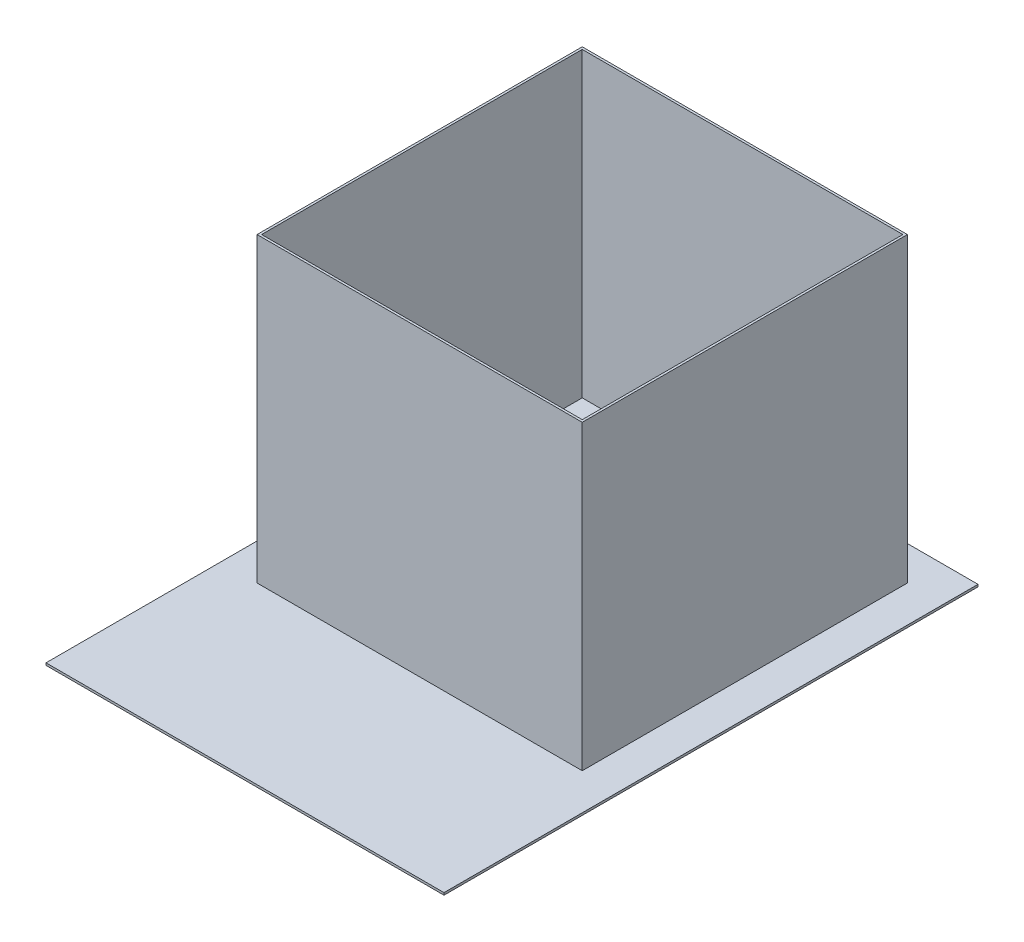
SolidWorks part; units mm, degrees
material "AISI 304"
ref_plane "Front" through (0, 0, 0) normal (0, 0, 1) x (1, 0, 0)
ref_plane "Top" through (0, 0, 0) normal (0, 1, 0) x (1, 0, 0)
ref_plane "Right" through (0, 0, 0) normal (1, 0, 0) x (0, 0, -1)
sketch "Croquis1" plane through (0, 0, 0) normal (0, 1, 0) x (1, 0, 0)
  line L0 (-0.6, -0.6) -> (85.6, -0.6)
  line L1 (0, 0) -> (85, 0)
  line L2 (0, 0) -> (0, 85)
  line L3 (0, 85) -> (85, 85)
  line L4 (85, 0) -> (85, 85)
  line L5 (0, 0) -> (85, 85) construction
  line L6 (0, 85) -> (85, 0) construction
  line L7 (85.6, -0.6) -> (85.6, 85.6)
  line L8 (-0.6, 85.6) -> (85.6, 85.6)
  line L9 (-0.6, -0.6) -> (-0.6, 85.6)
  point P5 (42.5, 42.5)
  dimension "D1" = 85
  dimension "D2" = 0.6
extrude "Saliente-Extruir1" add sketch "Croquis1" along normal blind 80
sketch "Croquis2" plane through (0, 0, 0) normal (0, -1, 0) x (1, 0, 0)
  line L0 (42.5, 0.6) -> (42.5, -85.6) construction
  line L1 (-0.6, 0.6) -> (85.6, 0.6) construction
  line L2 (85.6, -85.6) -> (-0.6, -85.6) construction
  line L3 (95.2536, -94.6568) -> (-10.2536, -94.6568)
  line L4 (-10.2536, -94.6568) -> (-10.2536, 46.8947)
  line L5 (-10.2536, 46.8947) -> (95.2536, 46.8947)
  line L6 (95.2536, -94.6568) -> (95.2536, 46.8947)
  point P11 (42.5, 46.8947)
  point P12 (42.5, -94.6568)
extrude "Saliente-Extruir2" add sketch "Croquis2" along normal blind 0.6
